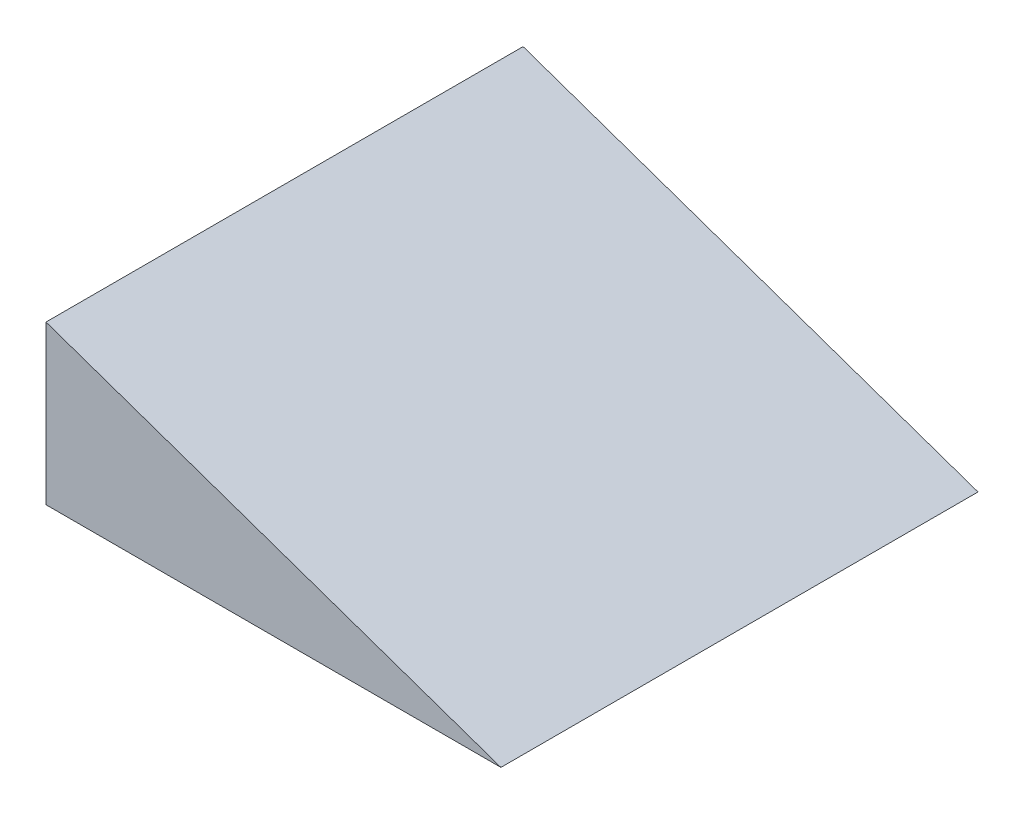
SolidWorks part; units mm, degrees
ref_plane "Front Plane" through (0, 0, 0) normal (0, 0, 1) x (1, 0, 0)
ref_plane "Top Plane" through (0, 0, 0) normal (0, 1, 0) x (1, 0, 0)
ref_plane "Right Plane" through (0, 0, 0) normal (1, 0, 0) x (0, 0, -1)
sketch "Sketch1" plane through (0, 0, 0) normal (0, 0, 1) x (1, 0, 0)
  line L0 (0, 0) -> (23, 0)
  line L1 (23, 0) -> (0, 8)
  line L2 (0, 8) -> (0, 0)
  dimension "D1" = 8
  dimension "D2" = 23
extrude "Boss-Extrude1" add sketch "Sketch1" along normal blind 24.12
